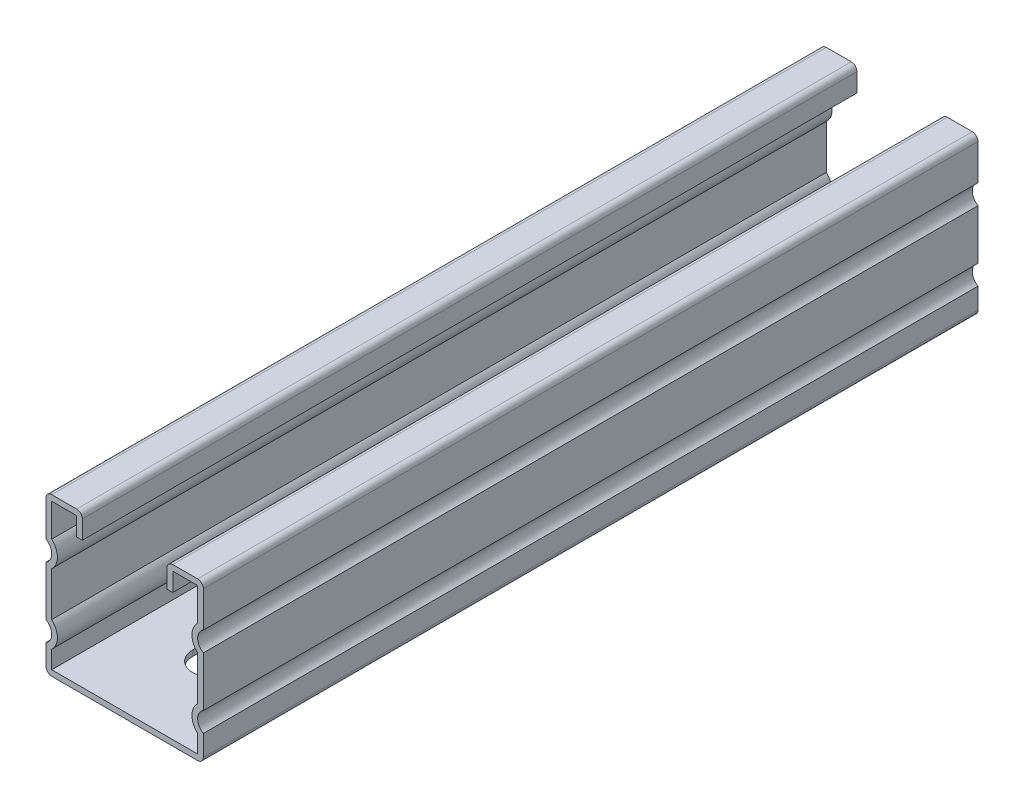
SolidWorks part; units mm, degrees
ref_plane "Plane1" through (0, 0, 0) normal (0, 0, 1) x (1, 0, 0)
ref_plane "Plane2" through (0, 0, 0) normal (0, 1, 0) x (1, 0, 0)
ref_plane "Plane3" through (0, 0, 0) normal (1, 0, 0) x (0, 0, -1)
sketch "Sketch1" plane through (0, 0, 0) normal (0, 0, 1) x (1, 0, 0)
  line L0 (-20.6375, 21.1074) -> (-20.6375, 11.7397)
  line L1 (-20.6375, 6.5483) -> (-20.6375, -6.5483)
  line L2 (-19.1389, -18.669) -> (19.1389, -18.669)
  line L3 (20.6375, -17.1704) -> (20.6375, -11.7397)
  line L4 (20.6375, 11.7397) -> (20.6375, 21.1074)
  line L5 (19.1389, 22.606) -> (12.6111, 22.606)
  line L6 (11.1125, 21.1074) -> (11.1125, 16.256)
  line L7 (-19.1389, 22.606) -> (-12.6111, 22.606)
  line L8 (-11.1125, 21.1074) -> (-11.1125, 16.256)
  line L9 (19.1389, -12.495) -> (19.1389, 12.495) construction
  line L10 (-19.1389, 12.495) -> (-19.1389, -12.495) construction
  line L11 (-12.6111, 21.1074) -> (-12.6111, 16.256)
  line L12 (-19.1389, 21.1074) -> (-12.6111, 21.1074)
  line L13 (-19.1389, 21.1074) -> (-19.1389, 12.495)
  line L14 (-19.1389, 5.793) -> (-19.1389, -5.793)
  line L15 (-19.1389, -17.1704) -> (19.1389, -17.1704)
  line L16 (19.1389, -17.1704) -> (19.1389, -12.495)
  line L17 (19.1389, 12.495) -> (19.1389, 21.1074)
  line L18 (19.1389, 21.1074) -> (12.6111, 21.1074)
  line L19 (12.6111, 21.1074) -> (12.6111, 16.256)
  line L20 (-12.6111, 16.256) -> (-11.1125, 16.256)
  line L21 (11.1125, 16.256) -> (12.6111, 16.256)
  line L22 (-10.16, 0) -> (12.7, 0) construction
  line L23 (-20.6375, -11.7397) -> (-20.6375, -17.1704)
  line L24 (-19.1389, -12.495) -> (-19.1389, -17.1704)
  line L25 (20.6375, -6.5483) -> (20.6375, 6.5483)
  line L26 (19.1389, -5.793) -> (19.1389, 5.793)
  arc A0 (20.6375, 11.7397) -> (20.6375, 6.5483) centre (22.1361, 9.144) ccw
  arc A1 (-20.6375, 6.5483) -> (-20.6375, 11.7397) centre (-22.1361, 9.144) ccw
  arc A2 (-12.6111, 22.606) -> (-11.1125, 21.1074) centre (-12.6111, 21.1074) cw
  arc A3 (-20.6375, 21.1074) -> (-19.1389, 22.606) centre (-19.1389, 21.1074) cw
  arc A4 (-19.1389, -18.669) -> (-20.6375, -17.1704) centre (-19.1389, -17.1704) cw
  arc A5 (20.6375, -17.1704) -> (19.1389, -18.669) centre (19.1389, -17.1704) cw
  arc A6 (19.1389, 22.606) -> (20.6375, 21.1074) centre (19.1389, 21.1074) cw
  arc A7 (11.1125, 21.1074) -> (12.6111, 22.606) centre (12.6111, 21.1074) cw
  arc A8 (-19.1389, 5.793) -> (-19.1389, 12.495) centre (-22.1361, 9.144) ccw
  arc A9 (19.1389, 12.495) -> (19.1389, 5.793) centre (22.1361, 9.144) ccw
  arc A10 (20.6375, -11.7397) -> (20.6375, -6.5483) centre (22.1361, -9.144) cw
  arc A11 (19.1389, -12.495) -> (19.1389, -5.793) centre (22.1361, -9.144) cw
  arc A12 (-19.1389, -5.793) -> (-19.1389, -12.495) centre (-22.1361, -9.144) cw
  arc A13 (-20.6375, -6.5483) -> (-20.6375, -11.7397) centre (-22.1361, -9.144) cw
  dimension "D9" = 2.9972
  dimension "D10" = 2.9972
  dimension "D1" = 20.6375
  dimension "Width" = 41.275
  dimension "base" = 18.669
  dimension "ToeHt" = 22.606
  dimension "D6" = 22.225
  dimension "edge" = 9.525
  dimension "Lip" = 6.35
  dimension "D2" = 9.525
  dimension "gauge" = 1.4986
extrude "Base-Extrude" add sketch "Sketch1" along normal blind 203.2
extrude "Slot" cut sketch "Sketch2" against normal through all
sketch "Sketch2" plane through (1.1214, -18.669, -18.7802) normal (0, -1, 0) x (1, 0, 0)
  line L0 (4.038, 97.3614) -> (4.038, 31.4802)
  line L1 (-6.2808, 31.4802) -> (-6.2808, 97.3614)
  arc A0 (-6.2808, 31.4802) -> (4.038, 31.4802) centre (-1.1214, 31.4802) ccw
  arc A1 (4.038, 97.3614) -> (-6.2808, 97.3614) centre (-1.1214, 97.3614) ccw
  dimension "D3" = 10.3187
  dimension "D1" = 12.7
  dimension "D2" = 65.8813
pattern_linear "LPattern1" count 2 spacing 101.6 along (0, 0, 1) of "Slot"
equation "\"D1@Sketch1\" = \"Width@Sketch1\" / 2"
equation "\"D6@Sketch1\" = \"Width@Sketch1\" - 2 * \"edge@Sketch1\""
equation "\"D10@Sketch1\" = 2 * \"gauge@Sketch1\""
equation "\"D9@Sketch1\" = \"D10@Sketch1\""
equation "\"D2@Sketch1\" = \"edge@Sketch1\""
equation "\"D1@LPattern1\" = \"D1@Base-Extrude\" / \"D3@LPattern1\""
